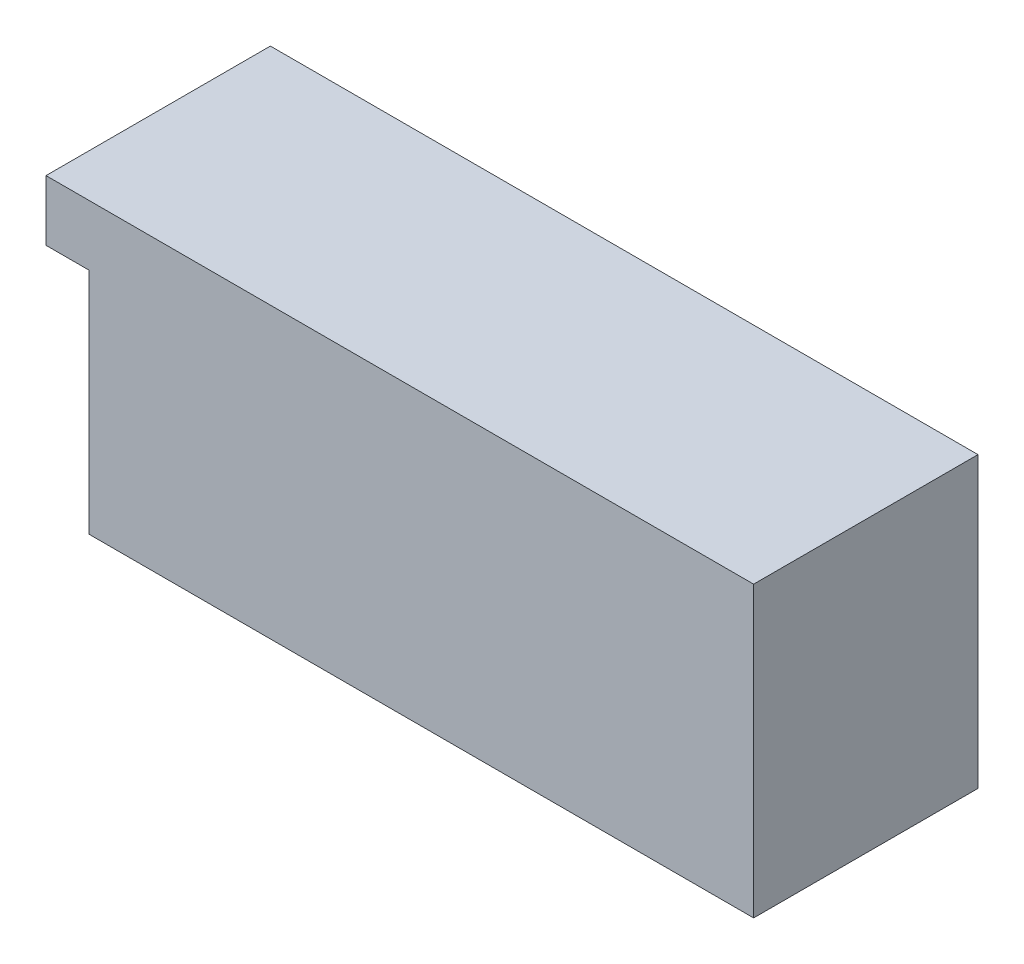
SolidWorks part; units mm, degrees
ref_plane "Front Plane" through (0, 0, 0) normal (0, 0, 1) x (1, 0, 0)
ref_plane "Top Plane" through (0, 0, 0) normal (0, 1, 0) x (1, 0, 0)
ref_plane "Right Plane" through (0, 0, 0) normal (1, 0, 0) x (0, 0, -1)
sketch "Sketch2" plane through (0, 0, 0) normal (0, 0, 1) x (1, 0, 0)
  line L1 (-38.5, -16.75) -> (38.5, -16.75)
  line L2 (-38.5, -16.75) -> (-38.5, 16.75)
  line L3 (-38.5, 16.75) -> (38.5, 16.75)
  line L4 (38.5, -16.75) -> (38.5, 16.75)
  line L5 (-38.5, -16.75) -> (38.5, 16.75) construction
  line L6 (-38.5, 16.75) -> (38.5, -16.75) construction
  point P0 (0, 0)
extrude "Boss-Extrude1" add sketch "Sketch2" along normal blind 26
sketch "Sketch3" plane through (-38.5, 0, 0) normal (-1, 0, 0) x (0, 0, 1)
  line L0 (26, 16.75) -> (26, -16.75) construction
  line L1 (0, 16.75) -> (26, 16.75)
  line L2 (0, 16.75) -> (0, 9.75)
  line L3 (0, 9.75) -> (26, 9.75)
  line L4 (26, 16.75) -> (26, 9.75)
  dimension "D1" = 7
extrude "Boss-Extrude2" add sketch "Sketch3" along normal blind 5
